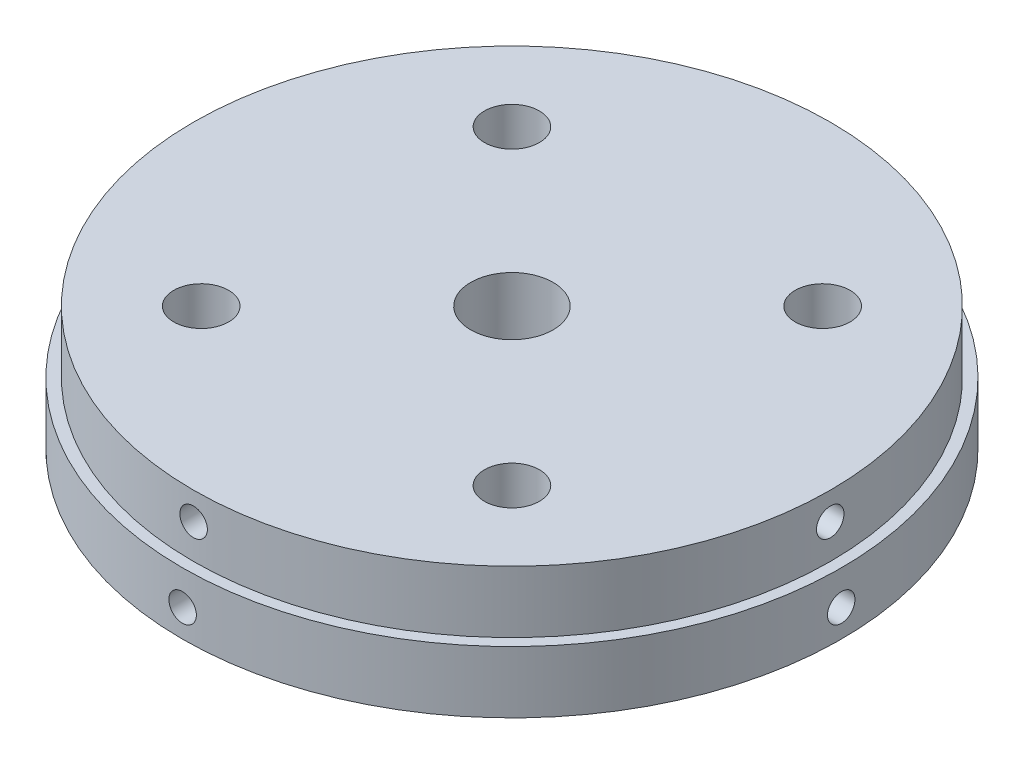
SolidWorks part; units mm, degrees
material "6061-T6 (SS)"
ref_plane "Front Plane" through (0, 0, 0) normal (0, 0, 1) x (1, 0, 0)
ref_plane "Top Plane" through (0, 0, 0) normal (0, 1, 0) x (1, 0, 0)
ref_plane "Right Plane" through (0, 0, 0) normal (1, 0, 0) x (0, 0, -1)
sketch "Sketch1" plane through (0, 0, 0) normal (0, 1, 0) x (1, 0, 0)
  circle A0 centre (0, 0) radius 76.2
  dimension "D1" = 152.4
extrude "Boss-Extrude1" add sketch "Sketch1" along normal blind 28.575
sketch "Sketch2" plane through (0, 28.575, 0) normal (0, 1, 0) x (1, 0, 0)
  circle A0 centre (0, 0) radius 9.525
  dimension "D1" = 19.05
extrude "Cut-Extrude1" cut sketch "Sketch2" against normal through all
ref_plane "Plane1" through (0, 0, 76.2) normal (0, 0, 1) x (1, 0, 0)
ref_plane "Plane2" through (0, 0, -69.85) normal (0, 0, 1) x (1, 0, 0)
sketch "Sketch30" plane through (0, 0, 76.2) normal (0, 0, 1) x (1, 0, 0)
  line L0 (0, 30.5674) -> (0, -2.7265) construction
  line L1 (76.2, 28.575) -> (-76.2, 28.575) construction
  circle A0 centre (0, 22.225) radius 3.175
  circle A1 centre (0, 6.35) radius 3.175
  dimension "D1" = 6.35
  dimension "D2" = 6.35
  dimension "D3" = 15.875
  dimension "D4" = 6.35
extrude "Cut-Extrude2" cut sketch "Sketch30" against normal blind 25.4
pattern_circular "CirPattern3" count 4 over 360 about axis through (0, 0, 0) along (0, 1, 0) of "Cut-Extrude2"
sketch "Sketch31" plane through (0, 28.575, 0) normal (0, 1, 0) x (1, 0, 0)
  line L0 (0, 76.2) -> (0, -76.2) construction
  line L1 (-76.2, 0) -> (76.2, 0) construction
  line L2 (53.8815, 53.8815) -> (-53.8815, -53.8815) construction
  line L3 (-53.8815, 53.8815) -> (53.8815, -53.8815) construction
  circle A0 centre (0, 0) radius 76.2 construction
  circle A1 centre (35.921, 35.921) radius 6.35
  dimension "D4" = 12.7
  dimension "D1" = 50.8
  dimension "D2" = 45
  dimension "D3" = 45
extrude "Cut-Extrude3" cut sketch "Sketch31" against normal through all
pattern_circular "CirPattern4" count 4 over 360 about axis through (0, 0, 0) along (0, 1, 0) of "Cut-Extrude3"
ref_axis "Axis1" through (0, 28.575, 0) along (0, -1, 0)
sketch "Sketch34" plane through (0, 0, 0) normal (0, 0, 1) x (1, 0, 0)
  line L1 (76.2, 28.575) -> (73.66, 28.575)
  line L2 (76.2, 28.575) -> (76.2, 14.2875)
  line L3 (76.2, 14.2875) -> (73.66, 14.2875)
  line L4 (73.66, 28.575) -> (73.66, 14.2875)
  dimension "D1" = 14.2875
  dimension "D2" = 2.54
revolve "Cut-Revolve1" cut sketch "Sketch34" angle 360 about axis through (0, 28.575, 0) along (0, -1, 0)
